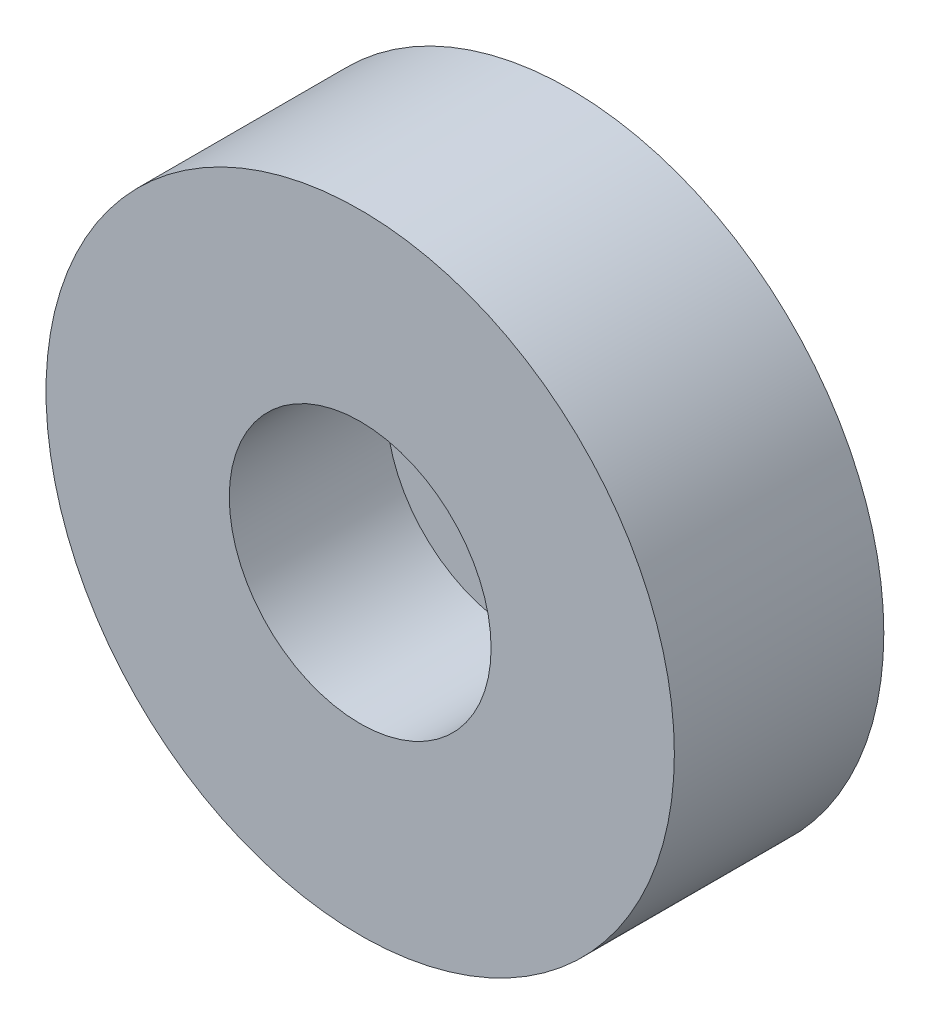
SolidWorks part; units mm, degrees
ref_plane "Ebene vorne" through (0, 0, 0) normal (0, 0, 1) x (1, 0, 0)
ref_plane "Ebene oben" through (0, 0, 0) normal (0, 1, 0) x (1, 0, 0)
ref_plane "Ebene rechts" through (0, 0, 0) normal (1, 0, 0) x (0, 0, -1)
sketch "Skizze1" plane through (0, 0, 0) normal (0, 0, 1) x (1, 0, 0)
  circle A0 centre (0, 0) radius 60
  dimension "D1" = 120
extrude "Aufsatz-Linear austragen1" add sketch "Skizze1" along normal blind 40
sketch "Skizze2" plane through (0, 0, 40) normal (0, 0, 1) x (1, 0, 0)
  circle A0 centre (0, 0) radius 25
extrude "Schnitt-Linear austragen1" cut sketch "Skizze2" against normal blind 30
